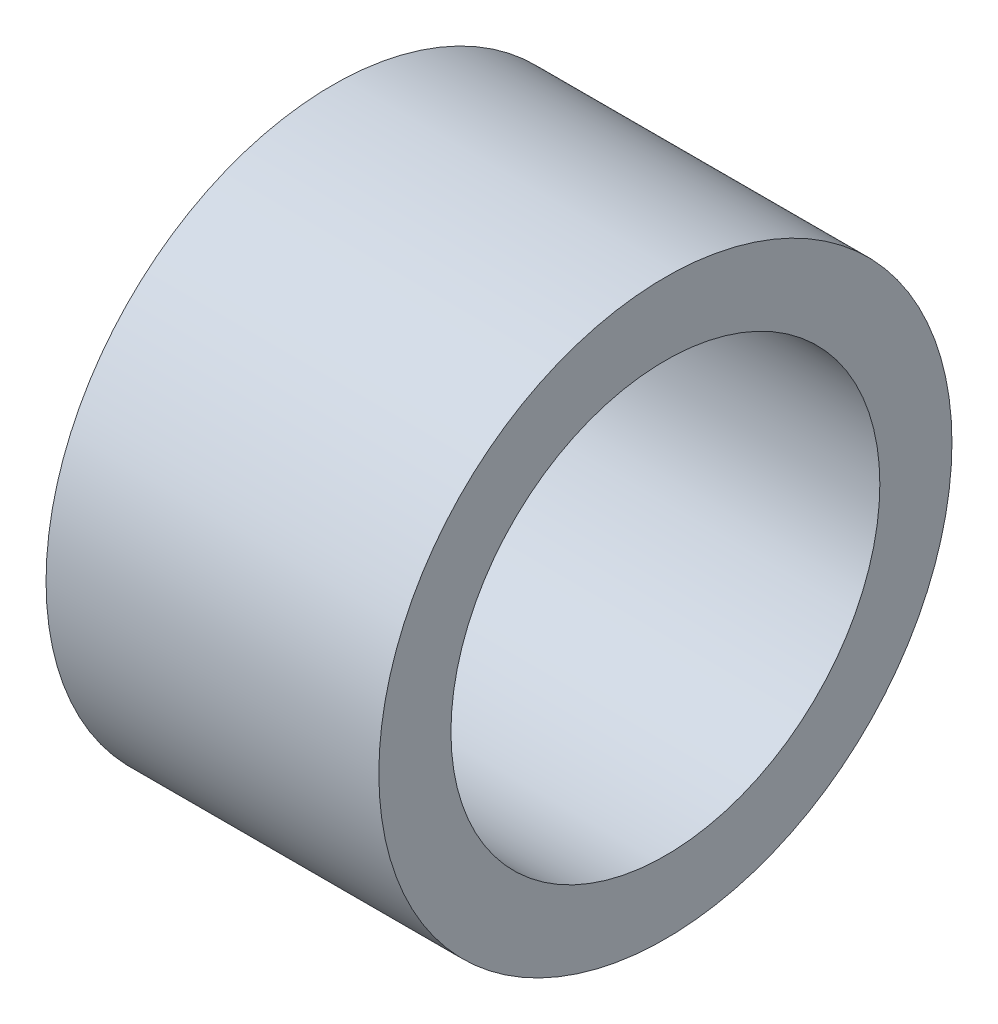
SolidWorks part; units mm, degrees
ref_plane "Front Plane" through (0, 0, 0) normal (0, 0, 1) x (1, 0, 0)
ref_plane "Top Plane" through (0, 0, 0) normal (0, 1, 0) x (1, 0, 0)
ref_plane "Right Plane" through (0, 0, 0) normal (1, 0, 0) x (0, 0, -1)
sketch "Sketch1" plane through (0, 0, 0) normal (1, 0, 0) x (0, 0, -1)
  circle A0 centre (0, 0) radius 7.75
  circle A1 centre (0, 0) radius 5.8
  dimension "D1" = 15.5
  dimension "D2" = 11.6
extrude "Boss-Extrude1" add sketch "Sketch1" along normal blind 9
